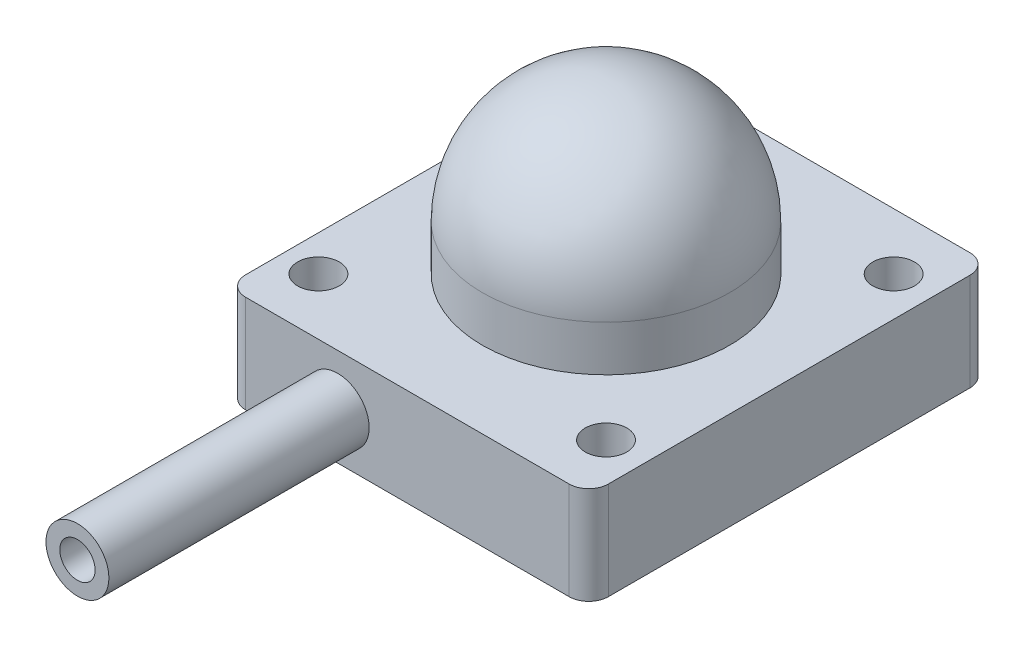
SolidWorks part; units mm, degrees
ref_plane "Front Plane" through (0, 0, 0) normal (0, 0, 1) x (1, 0, 0)
ref_plane "Top Plane" through (0, 0, 0) normal (0, 1, 0) x (1, 0, 0)
ref_plane "Right Plane" through (0, 0, 0) normal (1, 0, 0) x (0, 0, -1)
sketch "Sketch1" plane through (0, 0, 0) normal (0, 1, 0) x (1, 0, 0)
  line L0 (11.05, 11.05) -> (11.05, -11.05) construction
  line L2 (11.05, -11.05) -> (-11.05, -11.05) construction
  line L3 (-12.65, 11.05) -> (12.65, 11.05) construction
  line L4 (-11.05, 12.65) -> (-11.05, -12.65) construction
  line L11 (11.05, -11.05) -> (-11.05, 11.05) construction
  line L12 (11.05, 11.05) -> (-11.05, -11.05) construction
  line L13 (0, 11.05) -> (0, 11.0165) construction
  line L14 (-13.7915, 15.3963) -> (14.0689, 15.3963)
  line L15 (14.0689, 15.3963) -> (14.0689, -15.3963)
  line L16 (14.0689, -15.3963) -> (-13.7915, -15.3963)
  line L17 (-13.7915, -15.3963) -> (-13.7915, 15.3963)
  line L18 (-13.7915, 0) -> (0, 0) construction
  circle A0 centre (-11.05, 11.05) radius 1.6
  circle A1 centre (11.05, 11.05) radius 1.6
  circle A2 centre (-11.05, -11.05) radius 1.6
  circle A3 centre (11.05, -11.05) radius 1.6
extrude "Boss-Extrude1" add sketch "Sketch1" along normal blind 7.5
sketch "Sketch2" plane through (0, 7.5, 0) normal (0, 1, 0) x (1, 0, 0)
  circle A0 centre (0, 0) radius 9.5
extrude "Boss-Extrude2" add sketch "Sketch2" along normal blind 3.5
sketch "Sketch3" plane through (0, 11, 0) normal (0, 1, 0) x (1, 0, 0)
  line L0 (-9.5, 0) -> (9.5, 0)
  circle A1 centre (0, 0) radius 9.5
  arc A2 (9.5, 0) -> (-9.5, 0) centre (0, 0) ccw
  dimension "D1" = 0
revolve "Revolve3" add sketch "Sketch3" angle 180 about L0
fillet "Fillet1" radius 1.5 4 edges at (-13.7915, 3.75, -15.3963) (14.0689, 3.75, -15.3963) (14.0689, 3.75, 15.3963) (-13.7915, 3.75, 15.3963)
sketch "Sketch4" plane through (0, 0, 15.3963) normal (0, 0, 1) x (1, 0, 0)
  circle A0 centre (-5.2202, 3.5594) radius 2.416
  circle A1 centre (-5.2202, 3.5594) radius 1.3584
  point P3 (-5.2202, 3.5594)
extrude "Boss-Extrude3" add sketch "Sketch4" along normal blind 20
